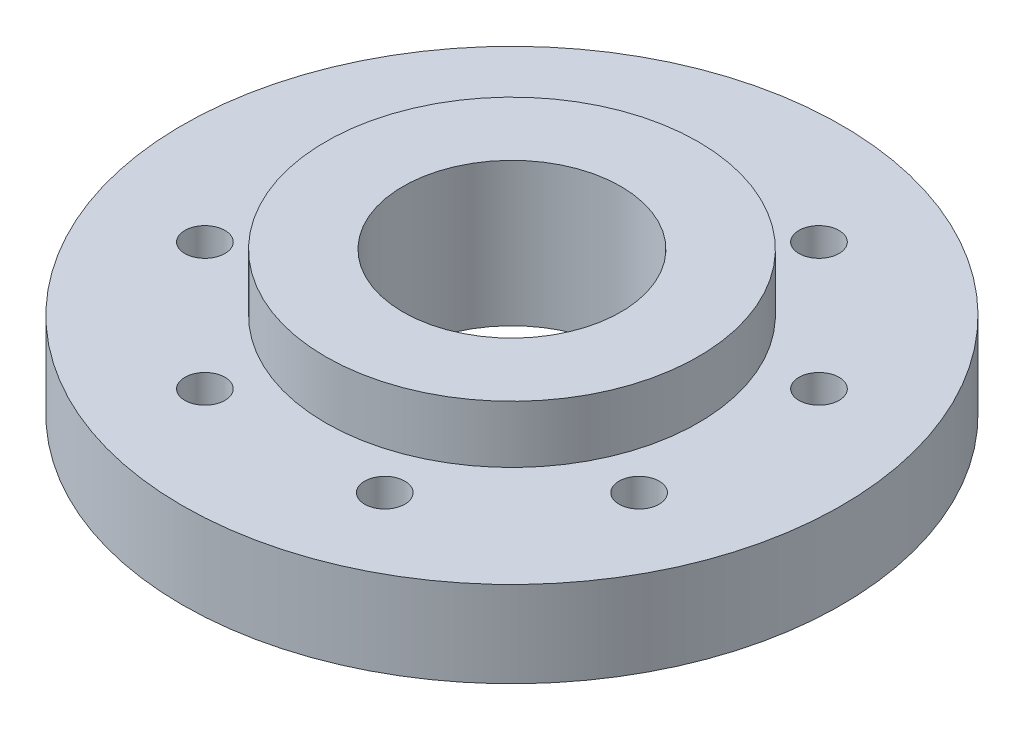
SolidWorks part; units mm, degrees
ref_plane "前视基准面" through (0, 0, 0) normal (0, 0, 1) x (1, 0, 0)
ref_plane "上视基准面" through (0, 0, 0) normal (0, 1, 0) x (1, 0, 0)
ref_plane "右视基准面" through (0, 0, 0) normal (1, 0, 0) x (0, 0, -1)
other "Configuration Table"
sketch "01_Flange_Profile" plane through (0, 0, 0) normal (0, 1, 0) x (1, 0, 0)
  circle A0 centre (0, 0) radius 115
  circle A1 centre (0, 0) radius 38
  circle A2 centre (75.7581, 31.38) radius 7
  circle A3 centre (31.38, 75.7581) radius 7
  circle A4 centre (-31.38, 75.7581) radius 7
  circle A5 centre (-75.7581, 31.38) radius 7
  circle A6 centre (-75.7581, -31.38) radius 7
  circle A7 centre (-31.38, -75.7581) radius 7
  circle A8 centre (31.38, -75.7581) radius 7
  circle A9 centre (75.7581, -31.38) radius 7
extrude "01_Flange_Extrude" add sketch "01_Flange_Profile" along normal blind 30
sketch "02_Hub_Profile" plane through (0, 0, 0) normal (0, 1, 0) x (1, 0, 0)
  circle A0 centre (0, 0) radius 65
  circle A1 centre (0, 0) radius 38
extrude "02_Locating_Hub" add sketch "02_Hub_Profile" along normal blind 50
